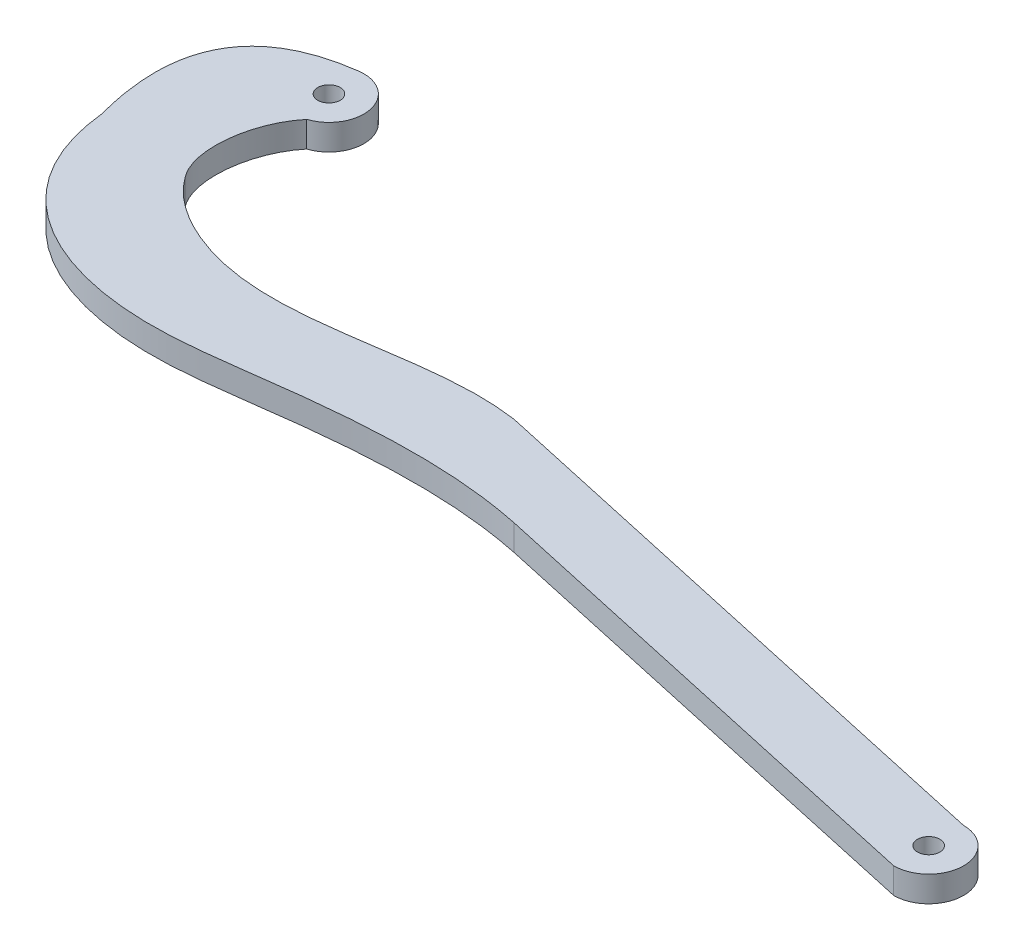
SolidWorks part; units mm, degrees
material "ABS PC"
ref_plane "Front Plane" through (0, 0, 0) normal (0, 0, 1) x (1, 0, 0)
ref_plane "Top Plane" through (0, 0, 0) normal (0, 1, 0) x (1, 0, 0)
ref_plane "Right Plane" through (0, 0, 0) normal (1, 0, 0) x (0, 0, -1)
sketch "Sketch1" plane through (0, 0, 0) normal (0, 1, 0) x (1, 0, 0)
  line L1 (2.3827, -0.88) -> (7.4459, -2.7499)
  line L2 (216.0155, -71.8405) -> (84.9851, -42.9779)
  line L3 (-2.54, 0) -> (87.0608, 0)
  line L5 (213.6328, -78.898) -> (216.0155, -79.778)
  line L6 (105.4232, -63.3548) -> (216.0155, -87.7155)
  circle A0 centre (0, 0) radius 2.54
  arc A1 (2.4906, -7.5366) -> (-0.9616, 7.879) centre (0, 0) ccw
  circle A2 centre (216.0155, -79.778) radius 2.54
  arc A3 (212.6805, -86.9809) -> (216.0155, -71.8405) centre (216.0155, -79.778) ccw
  spline S0 degree 2 poles (-0.9616, 7.879) (-30.9985, 4.0165) (-21.8784, -29.6751) knots 0 0 0 0.355275 0.355275 0.355275
  spline S1 degree 3 poles (-1.1263, -30.8191) (-0.76, -31.4894) (3.4694, -38.2197) (33.5488, -54.5348) (63.191, -39.7728) (84.9851, -42.9779) knots 0.174416 0.174416 0.174416 0.174416 0.196438 0.402513 1 1 1 1
  spline S2 degree 2 poles (5.7028, -2.1061) (6.7744, -1.0735) (7.9375, 0) knots 0.965212 0.965212 0.965212 1 1 1
  spline S3 degree 3 poles (2.4906, -7.5366) (-3.1771, -14.27) (-4.6828, -26.6903) (0.0947, -32.7683) knots 0.069848 0.069848 0.069848 0.069848 0.385912 0.385912 0.385912 0.385912
  spline S4 degree 3 poles (-21.8784, -29.6751) (-19.1757, -55.8612) (11.699, -69.0974) (59.1951, -61.6131) (86.7061, -59.43) (105.4232, -63.3548) knots 0 0 0 0 0.428303 0.609288 1 1 1 1
  dimension "D1" = 5.08
  dimension "D2" = 15.875
  dimension "D5" = 5.08
  dimension "D6" = 15.875
extrude "Boss-Extrude1" add sketch "Sketch1" along normal blind 5.842
